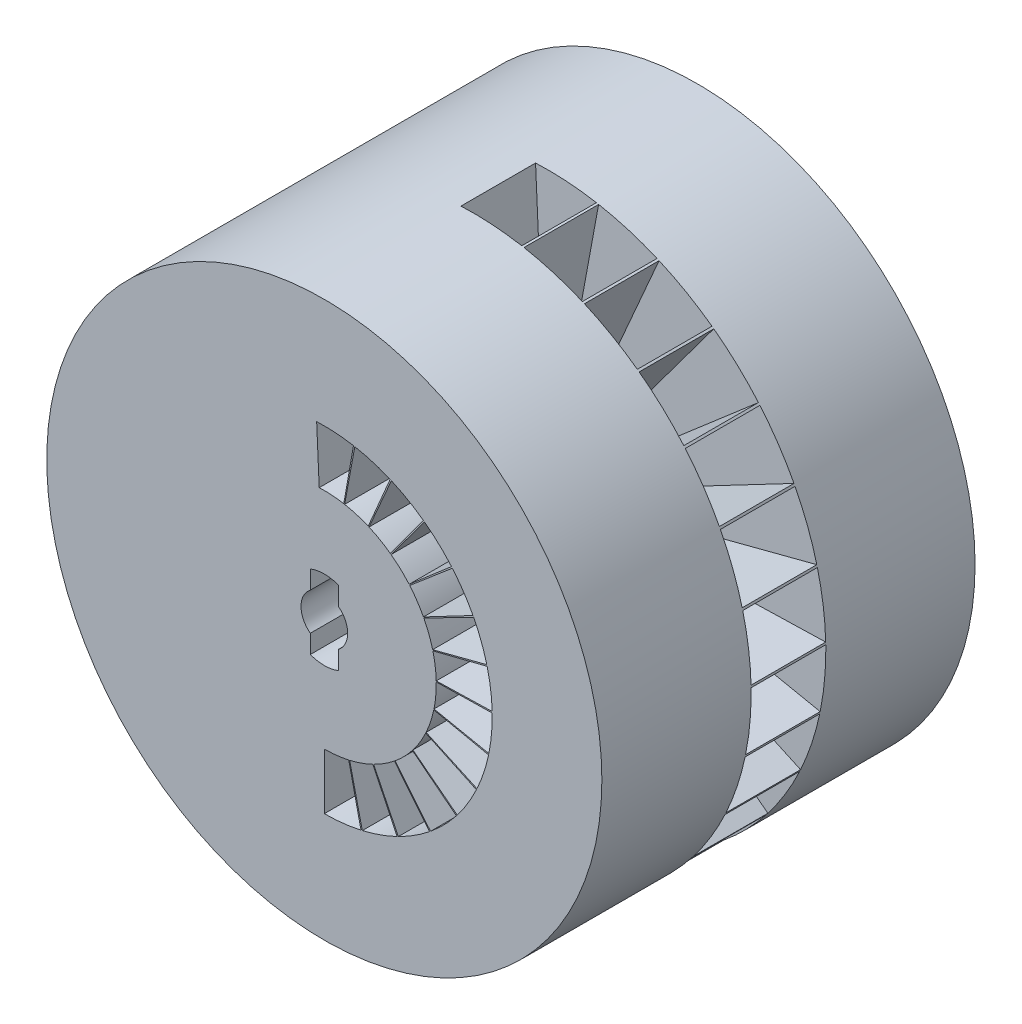
SolidWorks part; units mm, degrees
ref_plane "Front Plane" through (0, 0, 0) normal (0, 0, 1) x (1, 0, 0)
ref_plane "Top Plane" through (0, 0, 0) normal (0, 1, 0) x (1, 0, 0)
ref_plane "Right Plane" through (0, 0, 0) normal (1, 0, 0) x (0, 0, -1)
sketch "Sketch1" plane through (0, 0, 0) normal (0, 0, 1) x (1, 0, 0)
  line L0 (1.5, 2) -> (1.5, 3.9765)
  line L2 (1.5, -3.9765) -> (1.5, -2)
  line L4 (-1.5, -3.9765) -> (-1.5, -2)
  line L5 (-1.5, 2) -> (-1.5, 3.9765)
  circle A0 centre (0, 0) radius 29.75
  arc A1 (-1.5, 2) -> (-1.5, -2) centre (0, 0) ccw
  arc A2 (-1.5, -3.9765) -> (1.5, -3.9765) centre (0, 0) ccw
  arc A3 (1.5, -2) -> (1.5, 2) centre (0, 0) ccw
  arc A4 (1.5, 3.9765) -> (-1.5, 3.9765) centre (0, 0) ccw
  dimension "D1" = 59.5
  dimension "D2" = 5
  dimension "D3" = 8.5
  dimension "D4" = 3
extrude "Boss-Extrude1" add sketch "Sketch1" along normal blind 40
sketch "Sketch2" plane through (0, 0, 40) normal (0, 0, 1) x (1, 0, 0)
  line L0 (2.6211, -11.7103) -> (6.498, -29.0317)
  line L2 (0, -12) -> (0, -29.75)
  line L4 (6.498, -29.0317) -> (0, 0) construction
  line L6 (5.2026, -10.8135) -> (12.8982, -26.8086)
  line L7 (2.7151, -11.6888) -> (6.7312, -28.9785)
  line L8 (12.8982, -26.8086) -> (0, 0) construction
  line L9 (7.5144, -9.356) -> (18.6294, -23.195)
  line L10 (5.2894, -10.7714) -> (13.1133, -26.704)
  line L11 (18.6294, -23.195) -> (0, 0) construction
  line L12 (9.4364, -7.4131) -> (23.3944, -18.3784)
  line L13 (7.5893, -9.2953) -> (18.8152, -23.0445)
  line L14 (23.3944, -18.3784) -> (0, 0) construction
  line L15 (10.869, -5.0858) -> (26.946, -12.6086)
  line L16 (9.4957, -7.337) -> (23.5413, -18.1898)
  line L17 (26.946, -12.6086) -> (0, 0) construction
  line L18 (11.7378, -2.4947) -> (29.1, -6.1849)
  line L19 (10.9095, -4.9983) -> (27.0464, -12.3916)
  line L20 (29.1, -6.1849) -> (0, 0) construction
  line L21 (11.9979, 0.2257) -> (29.7447, 0.5596)
  line L22 (11.7575, -2.4003) -> (29.1488, -5.9508)
  line L23 (29.7447, 0.5596) -> (0, 0) construction
  line L24 (11.6357, 2.9345) -> (28.8467, 7.2751)
  line L25 (11.9957, 0.3222) -> (29.7393, 0.7987)
  line L26 (28.8467, 7.2751) -> (0, 0) construction
  line L27 (10.67, 5.4911) -> (26.4526, 13.6133)
  line L28 (11.6117, 3.028) -> (28.7873, 7.5068)
  line L29 (26.4526, 13.6133) -> (0, 0) construction
  line L30 (9.1509, 7.7629) -> (22.6865, 19.2454)
  line L31 (10.6255, 5.5767) -> (26.3423, 13.8255)
  line L32 (22.6865, 19.2454) -> (0, 0) construction
  line L33 (7.1571, 9.632) -> (17.7437, 23.8793)
  line L34 (9.0882, 7.8362) -> (22.531, 19.4272)
  line L35 (17.7437, 23.8793) -> (0, 0) construction
  line L36 (4.7922, 11.0016) -> (11.8807, 27.2748)
  line L37 (7.0795, 9.6892) -> (17.5512, 24.0212)
  line L38 (11.8807, 27.2748) -> (0, 0) construction
  line L39 (2.1787, 11.8006) -> (5.4014, 29.2556)
  line L40 (4.7036, 11.0398) -> (11.661, 27.3694)
  line L41 (5.4014, 29.2556) -> (0, 0) construction
  line L42 (-0.5478, 11.9875) -> (-1.358, 29.719)
  line L43 (2.0838, 11.8177) -> (5.166, 29.298)
  line L44 (-1.358, 29.719) -> (0, 0) construction
  line L45 (6.498, -29.0317) -> (6.7312, -28.9785) construction
  arc A0 (6.498, -29.0317) -> (0, -29.75) centre (0, 0) cw
  circle A1 centre (0, 0) radius 29.75 construction
  arc A2 (2.6211, -11.7103) -> (0, -12) centre (0, 0) cw
  arc A3 (12.8982, -26.8086) -> (6.7312, -28.9785) centre (0, 0) cw
  arc A4 (5.2026, -10.8135) -> (2.7151, -11.6888) centre (0, 0) cw
  arc A5 (18.6294, -23.195) -> (13.1133, -26.704) centre (0, 0) cw
  arc A6 (7.5144, -9.356) -> (5.2894, -10.7714) centre (0, 0) cw
  arc A7 (23.3944, -18.3784) -> (18.8152, -23.0445) centre (0, 0) cw
  arc A8 (9.4364, -7.4131) -> (7.5893, -9.2953) centre (0, 0) cw
  arc A9 (26.946, -12.6086) -> (23.5413, -18.1898) centre (0, 0) cw
  arc A10 (10.869, -5.0858) -> (9.4957, -7.337) centre (0, 0) cw
  arc A11 (29.1, -6.1849) -> (27.0464, -12.3916) centre (0, 0) cw
  arc A12 (11.7378, -2.4947) -> (10.9095, -4.9983) centre (0, 0) cw
  arc A13 (29.7447, 0.5596) -> (29.1488, -5.9508) centre (0, 0) cw
  arc A14 (11.9979, 0.2257) -> (11.7575, -2.4003) centre (0, 0) cw
  arc A15 (28.8467, 7.2751) -> (29.7393, 0.7987) centre (0, 0) cw
  arc A16 (11.6357, 2.9345) -> (11.9957, 0.3222) centre (0, 0) cw
  arc A17 (26.4526, 13.6133) -> (28.7873, 7.5068) centre (0, 0) cw
  arc A18 (10.67, 5.4911) -> (11.6117, 3.028) centre (0, 0) cw
  arc A19 (22.6865, 19.2454) -> (26.3423, 13.8255) centre (0, 0) cw
  arc A20 (9.1509, 7.7629) -> (10.6255, 5.5767) centre (0, 0) cw
  arc A21 (17.7437, 23.8793) -> (22.531, 19.4272) centre (0, 0) cw
  arc A22 (7.1571, 9.632) -> (9.0882, 7.8362) centre (0, 0) cw
  arc A23 (11.8807, 27.2748) -> (17.5512, 24.0212) centre (0, 0) cw
  arc A24 (4.7922, 11.0016) -> (7.0795, 9.6892) centre (0, 0) cw
  arc A25 (5.4014, 29.2556) -> (11.661, 27.3694) centre (0, 0) cw
  arc A26 (2.1787, 11.8006) -> (4.7036, 11.0398) centre (0, 0) cw
  arc A27 (-1.358, 29.719) -> (5.166, 29.298) centre (0, 0) cw
  arc A28 (-0.5478, 11.9875) -> (2.0838, 11.8177) centre (0, 0) cw
  point P63 (0, 0)
  dimension "D1" = 12
extrude "Cut-Extrude1" cut sketch "Sketch2" against normal blind 4 and the other way blind 4 from offset 20 offset against normal yes
sketch "Sketch3" plane through (0, 0, 40) normal (0, 0, 1) x (1, 0, 0)
  line L0 (0, -12) -> (0, -29.75) construction
  line L2 (0, -12) -> (0, -18)
  line L4 (2.6211, -11.7103) -> (3.9316, -17.5654)
  line L5 (6.498, -29.0317) -> (2.6211, -11.7103) construction
  line L6 (2.7151, -11.6888) -> (4.0727, -17.5332)
  line L7 (5.2026, -10.8135) -> (7.804, -16.2203)
  line L8 (5.2894, -10.7714) -> (7.9341, -16.157)
  line L9 (7.5144, -9.356) -> (11.2716, -14.034)
  line L10 (7.5893, -9.2953) -> (11.384, -13.9429)
  line L11 (9.4364, -7.4131) -> (14.1546, -11.1197)
  line L12 (9.4957, -7.337) -> (14.2435, -11.0056)
  line L13 (10.869, -5.0858) -> (16.3034, -7.6288)
  line L14 (10.9095, -4.9983) -> (16.3642, -7.4974)
  line L15 (11.7378, -2.4947) -> (17.6067, -3.7421)
  line L16 (11.7575, -2.4003) -> (17.6362, -3.6005)
  line L17 (11.9979, 0.2257) -> (17.9968, 0.3386)
  line L18 (11.9957, 0.3222) -> (17.9935, 0.4833)
  line L19 (11.6357, 2.9345) -> (17.4535, 4.4018)
  line L20 (11.6117, 3.028) -> (17.4175, 4.5419)
  line L21 (10.67, 5.4911) -> (16.0049, 8.2366)
  line L22 (10.6255, 5.5767) -> (15.9382, 8.365)
  line L23 (9.1509, 7.7629) -> (13.7263, 11.6443)
  line L24 (9.0882, 7.8362) -> (13.6322, 11.7543)
  line L25 (7.1571, 9.632) -> (10.7357, 14.448)
  line L26 (7.0795, 9.6892) -> (10.6192, 14.5338)
  line L27 (4.7922, 11.0016) -> (7.1883, 16.5024)
  line L28 (4.7036, 11.0398) -> (7.0554, 16.5596)
  line L29 (2.1787, 11.8006) -> (3.2681, 17.7008)
  line L30 (2.0838, 11.8177) -> (3.1257, 17.7265)
  line L31 (-0.5478, 11.9875) -> (-0.8217, 17.9812)
  arc A0 (2.6211, -11.7103) -> (0, -12) centre (0, 0) cw
  arc A1 (3.9316, -17.5654) -> (0, -18) centre (0, 0) cw
  arc A2 (5.2026, -10.8135) -> (2.7151, -11.6888) centre (0, 0) cw
  arc A3 (7.804, -16.2203) -> (4.0727, -17.5332) centre (0, 0) cw
  arc A4 (7.5144, -9.356) -> (5.2894, -10.7714) centre (0, 0) cw
  arc A5 (11.2716, -14.034) -> (7.9341, -16.157) centre (0, 0) cw
  arc A6 (9.4364, -7.4131) -> (7.5893, -9.2953) centre (0, 0) cw
  arc A7 (14.1546, -11.1197) -> (11.384, -13.9429) centre (0, 0) cw
  arc A8 (10.869, -5.0858) -> (9.4957, -7.337) centre (0, 0) cw
  arc A9 (16.3034, -7.6288) -> (14.2435, -11.0056) centre (0, 0) cw
  arc A10 (11.7378, -2.4947) -> (10.9095, -4.9983) centre (0, 0) cw
  arc A11 (17.6067, -3.7421) -> (16.3642, -7.4974) centre (0, 0) cw
  arc A12 (11.9979, 0.2257) -> (11.7575, -2.4003) centre (0, 0) cw
  arc A13 (17.9968, 0.3386) -> (17.6362, -3.6005) centre (0, 0) cw
  arc A14 (11.6357, 2.9345) -> (11.9957, 0.3222) centre (0, 0) cw
  arc A15 (17.4535, 4.4018) -> (17.9935, 0.4833) centre (0, 0) cw
  arc A16 (10.67, 5.4911) -> (11.6117, 3.028) centre (0, 0) cw
  arc A17 (16.0049, 8.2366) -> (17.4175, 4.5419) centre (0, 0) cw
  arc A18 (9.1509, 7.7629) -> (10.6255, 5.5767) centre (0, 0) cw
  arc A19 (13.7263, 11.6443) -> (15.9382, 8.365) centre (0, 0) cw
  arc A20 (7.1571, 9.632) -> (9.0882, 7.8362) centre (0, 0) cw
  arc A21 (10.7357, 14.448) -> (13.6322, 11.7543) centre (0, 0) cw
  arc A22 (4.7922, 11.0016) -> (7.0795, 9.6892) centre (0, 0) cw
  arc A23 (7.1883, 16.5024) -> (10.6192, 14.5338) centre (0, 0) cw
  arc A24 (2.1787, 11.8006) -> (4.7036, 11.0398) centre (0, 0) cw
  arc A25 (3.2681, 17.7008) -> (7.0554, 16.5596) centre (0, 0) cw
  arc A26 (-0.5478, 11.9875) -> (2.0838, 11.8177) centre (0, 0) cw
  arc A27 (-0.8217, 17.9812) -> (3.1257, 17.7265) centre (0, 0) cw
  point P68 (0, 0)
  dimension "D1" = 18
  dimension "D2" = 12
extrude "Cut-Extrude3" cut sketch "Sketch3" against normal blind 16
